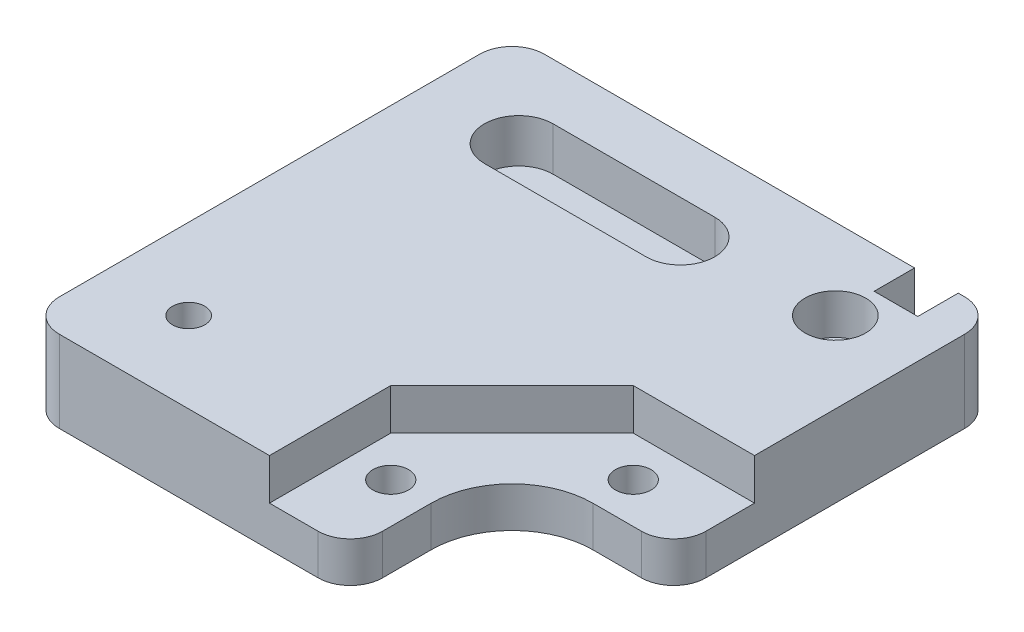
SolidWorks part; units mm, degrees
ref_plane "Front Plane" through (0, 0, 0) normal (0, 0, 1) x (1, 0, 0)
ref_plane "Top Plane" through (0, 0, 0) normal (0, 1, 0) x (1, 0, 0)
ref_plane "Right Plane" through (0, 0, 0) normal (1, 0, 0) x (0, 0, -1)
sketch "Sketch1" plane through (0, 0, 0) normal (0, 1, 0) x (1, 0, 0)
  line L0 (0, 0) -> (0, 20)
  line L1 (0, 0) -> (-40, 0)
  line L2 (20, 20) -> (20, 60)
  line L3 (20, 60) -> (-40, 60)
  line L4 (-40, 0) -> (-40, 60)
  line L5 (0, 20) -> (20, 20)
  line L6 (-10, 60) -> (-10, 0) construction
  line L7 (-40, 30) -> (20, 30) construction
  line L8 (20, 40) -> (0, 40) construction
  line L9 (0, 40) -> (-20, 20) construction
  line L10 (-20, 20) -> (-20, 0) construction
  line L15 (-10, 30) -> (0, 20) construction
  circle A0 centre (-28, 48.8332) radius 2.5 construction
  circle A1 centre (10, 25) radius 2.2
  circle A2 centre (-5, 10) radius 2.2
  point P18 (-10, 30)
  point P60 (20, 40)
  dimension "D4" = 11.1668
  dimension "D5" = 5
  dimension "D8" = 5
  dimension "D9" = 4.4
  dimension "D1" = 60
  dimension "D2" = 40
  dimension "D3" = 12
  dimension "D6" = 20
  dimension "D7" = 10
extrude "Boss-Extrude1" add sketch "Sketch1" along normal blind 10.1
sketch "Sketch4" plane through (0, 10.1, 0) normal (0, 1, 0) x (1, 0, 0)
  line L0 (-28, 53.0832) -> (-8, 53.0832)
  line L1 (-28, 44.5832) -> (-8, 44.5832)
  line L2 (-28, 53.0832) -> (-28, 44.5832) construction
  line L3 (-8, 53.0832) -> (-8, 44.5832) construction
  line L5 (-40, 60) -> (-40, 0) construction
  line L6 (-28, 44.5832) -> (-28, 53.0832) construction
  arc A1 (-28, 53.0832) -> (-28, 44.5832) centre (-28, 48.8332) ccw
  arc A2 (-8, 44.5832) -> (-8, 53.0832) centre (-8, 48.8332) ccw
  arc A3 (-8, 53.0832) -> (-8, 44.5832) centre (-8, 48.8332) ccw construction
  arc A4 (-28, 44.5832) -> (-28, 53.0832) centre (-28, 48.8332) ccw construction
  point P7 (-28, 48.8332)
  point P13 (-11.299, 48.1141)
  point P14 (-28, 48.8332)
  dimension "D1" = 8.5
  dimension "D2" = 20
extrude "Cut-Extrude2" cut sketch "Sketch4" against normal blind 5.4
sketch "Sketch7" plane through (0, 10.1, 0) normal (0, 1, 0) x (1, 0, 0)
  line L0 (0, 0) -> (20, 0) construction
  line L1 (20, 0) -> (20, 20) construction
  line L2 (20, 20) -> (20, 60) construction
  line L3 (0, 0) -> (0, 20) construction
  line L4 (20, 0) -> (-10, 0)
  line L5 (20, 0) -> (20, 30)
  line L6 (20, 30) -> (5, 30)
  line L7 (-10, 0) -> (-10, 15)
  line L8 (-10, 15) -> (5, 30)
  line L9 (-10, 15) -> (-10, 30) construction
  line L10 (5, 30) -> (-10, 30) construction
  point P14 (10.5316, 30)
  point P15 (-10, 9.0044)
  point P17 (-10, 14.2703)
  dimension "D1" = 10
  dimension "D2" = 15
extrude "Cut-Extrude4" cut sketch "Sketch7" against normal blind 5.1
sketch "Sketch9" plane through (0, 10.1, 0) normal (0, 1, 0) x (1, 0, 0)
  line L0 (0, 10) -> (-40, 10) construction
  line L1 (0, 0) -> (0, 20) construction
  line L2 (-40, 60) -> (-40, 0) construction
  line L3 (-40, 60) -> (0, 20) construction
  circle A0 centre (-30, 10) radius 2
  circle A1 centre (10, 50) radius 2
  dimension "D2" = 4
  dimension "D1" = 10
extrude "Cut-Extrude5" cut sketch "Sketch9" against normal through all
sketch "Sketch10" plane through (0, 10.1, 0) normal (0, 1, 0) x (1, 0, 0)
  circle A0 centre (10, 50) radius 3.75
  dimension "D1" = 7.5
extrude "Cut-Extrude6" cut sketch "Sketch10" against normal blind 5
fillet "Fillet2" radius 10 1 edges at (0, 2.5, -20)
fillet "Fillet3" radius 4 5 edges at (-40, 5.05, 0) (-40, 5.05, -60) (0, 2.5, 0) (20, 2.5, -20) (20, 5.05, -60)
sketch "Sketch11" plane through (0, 0, -60) normal (0, 0, -1) x (-1, 0, 0)
  line L0 (-12.5, 10.1) -> (-12.5, 1.8) construction
  line L1 (-16, 10.1) -> (36, 10.1) construction
  line L2 (-16, 10.1) -> (-16, 0) construction
  line L3 (-16, 5) -> (-15.2, 5)
  line L4 (-16, 5) -> (-16, 1.8)
  line L5 (-16, 1.8) -> (-9, 1.8)
  line L6 (-9, 5) -> (-9, 1.8)
  line L7 (-9.8, 5) -> (-9, 5)
  line L8 (-15.2, 10.1) -> (-9.8, 10.1)
  line L9 (-15.2, 10.1) -> (-15.2, 5)
  line L11 (-9.8, 10.1) -> (-9.8, 5)
  point P10 (-12.5, 1.8)
  point P15 (-12.5, 10.1)
  dimension "D1" = 7
  dimension "D2" = 3.2
  dimension "D3" = 8.3
  dimension "D4" = 2.7
extrude "Cut-Extrude7" cut sketch "Sketch11" against normal blind 5
